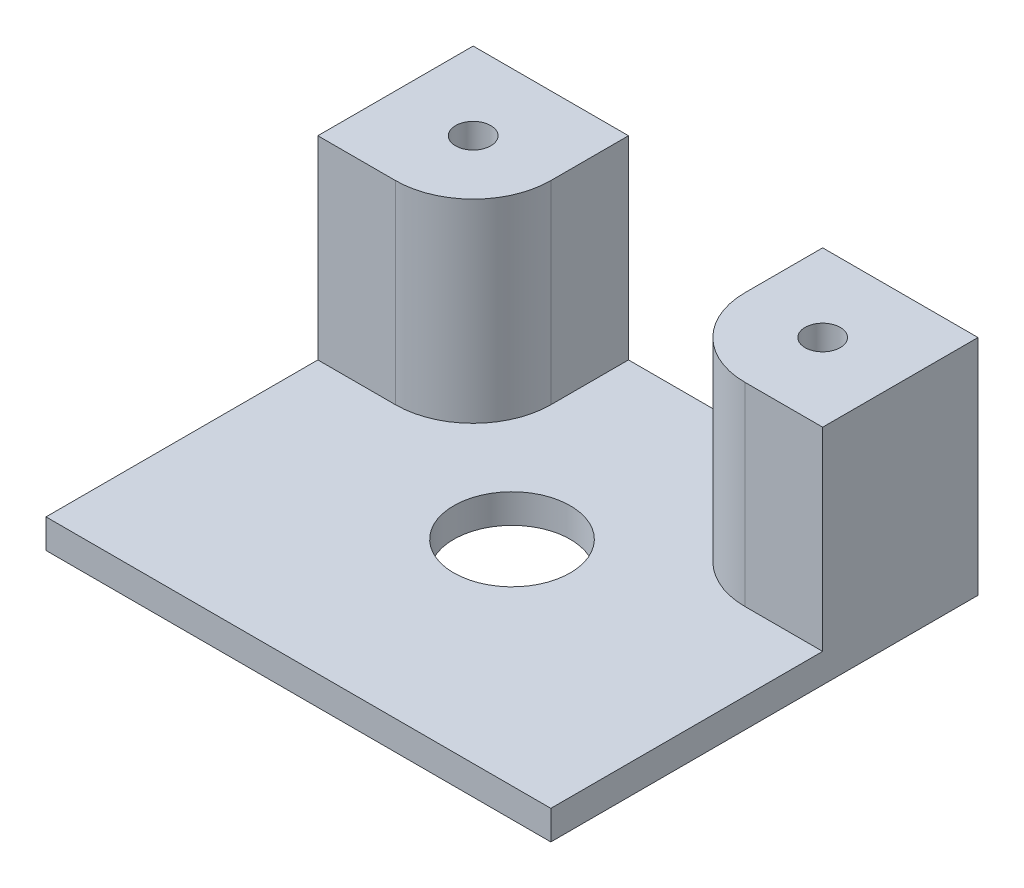
SolidWorks part; units mm, degrees
material "AISI 1020"
ref_plane "Front Plane" through (0, 0, 0) normal (0, 0, 1) x (1, 0, 0)
ref_plane "Top Plane" through (0, 0, 0) normal (0, 1, 0) x (1, 0, 0)
ref_plane "Right Plane" through (0, 0, 0) normal (1, 0, 0) x (0, 0, -1)
sketch "Sketch1" plane through (0, 0, 0) normal (0, 1, 0) x (1, 0, 0)
  line L1 (-82.55, -69.85) -> (82.55, -69.85)
  line L2 (-82.55, -69.85) -> (-82.55, 69.85)
  line L3 (-82.55, 69.85) -> (82.55, 69.85)
  line L4 (82.55, -69.85) -> (82.55, 69.85)
  line L5 (-82.55, -69.85) -> (82.55, 69.85) construction
  line L6 (-82.55, 69.85) -> (82.55, -69.85) construction
  point P0 (0, 0)
  dimension "D1" = 139.7
  dimension "D2" = 165.1
extrude "Boss-Extrude1" add sketch "Sketch1" along normal blind 9.525
sketch "Sketch2" plane through (0, 9.525, 0) normal (0, 1, 0) x (1, 0, 0)
  line L1 (-82.55, 69.85) -> (-31.75, 69.85)
  line L2 (-82.55, 69.85) -> (-82.55, 19.05)
  line L3 (-82.55, 19.05) -> (-31.75, 19.05)
  line L4 (-31.75, 69.85) -> (-31.75, 19.05)
  dimension "D1" = 50.8
  dimension "D2" = 50.8
extrude "Boss-Extrude2" add sketch "Sketch2" along normal blind 63.5
hole_wizard "1/2-20 Tapped Hole1" positions "Sketch4" profile "Sketch3" tap size "1/2-20" standard "Ansi Inch"
sketch "Sketch4" plane through (0, 73.025, 0) normal (0, 1, 0) x (-1, 0, 0)
  line L0 (82.55, -19.05) -> (31.75, -69.85) construction
  point P0 (57.15, -44.45)
sketch "Sketch3" plane through (-57.15, 73.025, -44.45) normal (1, 0, 0) x (0, 0, 1)
  line L0 (0, 0) -> (0, 35.2076)
  line L1 (0, 35.2076) -> (5.7544, 31.75)
  line L2 (5.7544, 31.75) -> (5.7544, 0)
  line L5 (5.7544, 0) -> (0, 0)
  line L10 (0, 35.2076) -> (-5.7544, 31.75) construction
  line L11 (0, -6.35) -> (0, 107.95) construction
  dimension "Tap Drill Dia." = 11.5087
  dimension "Tap Drill Depth" = 31.75
  dimension "Drill Angle" = 118
cosmetic thread "Hole Thread1" parameters "D1"=25.4, "D2"=12.7
fillet "Fillet1" radius 25.4 1 edges at (-31.75, 41.275, -19.05)
mirror "Mirror1" about plane through (0, 0, 0) normal (1, 0, 0) of "Boss-Extrude2", "1/2-20 Tapped Hole1", "Fillet1"
sketch "Sketch5" plane through (0, 9.525, 0) normal (0, 1, 0) x (1, 0, 0)
  line L0 (-82.55, -69.85) -> (82.55, -69.85) construction
  line L1 (82.55, -69.85) -> (82.55, 19.05) construction
  circle A0 centre (0, 0) radius 19.05
  dimension "D1" = 38.1
  dimension "D2" = 69.85
  dimension "D3" = 82.55
extrude "base hole" cut sketch "Sketch5" against normal through all
equation "\"Base Length\" = \"D2@Sketch1\""
equation "\"D1@Sketch1\"= \"Base Length\" - 1"
equation "\"Base Width\"= \"D1@Sketch1\""
equation "\"D3@Sketch5\" = \"Base Length\" / 2"
equation "\"D2@Sketch5\"= \"Base Width\" / 2"
